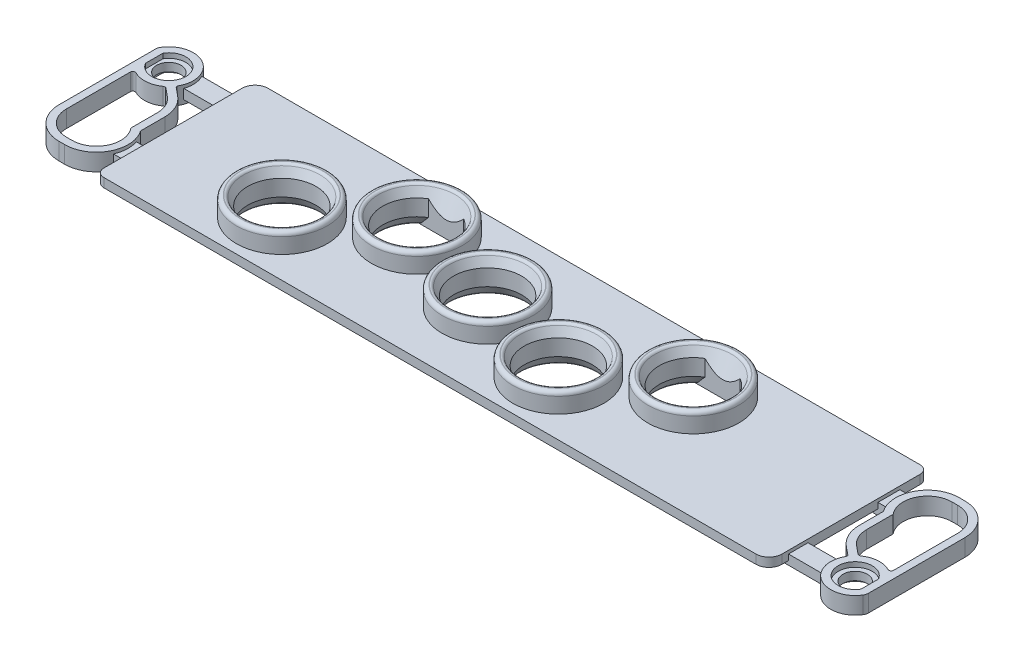
SolidWorks part; units mm, degrees
ref_plane "Front Plane" through (0, 0, 0) normal (0, 0, 1) x (1, 0, 0)
ref_plane "Top Plane" through (0, 0, 0) normal (0, 1, 0) x (1, 0, 0)
ref_plane "Right Plane" through (0, 0, 0) normal (1, 0, 0) x (0, 0, -1)
ref_plane "Plane1" through (0, 0, 0) normal (0, 1, 0) x (1, 0, 0)
sketch "Sketch1" plane through (0, 0, 0) normal (0, 1, 0) x (1, 0, 0)
  line L0 (-18.7, -4.9) -> (21.4, -4.9)
  line L1 (22.2, -4.1) -> (22.2, 4.4)
  line L2 (21.7, 4.9) -> (-18.4, 4.9)
  line L3 (-19.2, 4.1) -> (-19.2, -4.4)
  arc A0 (-19.2, -4.4) -> (-18.7, -4.9) centre (-18.7, -4.4) ccw
  arc A1 (21.4, -4.9) -> (22.2, -4.1) centre (21.4, -4.1) ccw
  arc A2 (22.2, 4.4) -> (21.7, 4.9) centre (21.7, 4.4) ccw
  arc A3 (-18.4, 4.9) -> (-19.2, 4.1) centre (-18.4, 4.1) ccw
extrude "Boss-Extrude1" add sketch "Sketch1" along normal blind 0.55
ref_plane "Plane2" through (0, 0, 0) normal (0, 0, 1) x (1, 0, 0)
sketch "Sketch2" plane through (0, 0, 0) normal (0, 0, 1) x (1, 0, 0)
  line L0 (20.349, 0) -> (20.9111, -0.5621)
  line L1 (21.1233, -0.65) -> (21.25, -0.65)
  line L2 (21.45, -0.45) -> (21.45, 0)
  line L3 (21.45, 0) -> (20.349, 0)
  arc A0 (20.9111, -0.5621) -> (21.1233, -0.65) centre (21.1233, -0.35) ccw
  arc A1 (21.25, -0.65) -> (21.45, -0.45) centre (21.25, -0.45) ccw
extrude "Boss-Extrude2" add sketch "Sketch2" against normal blind 3.95 and the other way blind 3.95
ref_plane "Plane3" through (0, 0, 0) normal (0, 0, 1) x (1, 0, 0)
sketch "Sketch3" plane through (0, 0, 0) normal (0, 0, 1) x (1, 0, 0)
  line L0 (-18.25, -0.65) -> (-18.1233, -0.65)
  line L1 (-17.9111, -0.5621) -> (-17.349, 0)
  line L2 (-17.349, 0) -> (-18.45, 0)
  line L3 (-18.45, 0) -> (-18.45, -0.45)
  arc A0 (-18.45, -0.45) -> (-18.25, -0.65) centre (-18.25, -0.45) ccw
  arc A1 (-18.1233, -0.65) -> (-17.9111, -0.5621) centre (-18.1233, -0.35) ccw
extrude "Boss-Extrude3" add sketch "Sketch3" against normal blind 3.95 and the other way blind 3.95
ref_plane "Plane4" through (0, 0, 0) normal (0, 0, 1) x (1, 0, 0)
sketch "Sketch4" plane through (0, 0, 0) normal (0, 0, 1) x (1, 0, 0)
  line L0 (17.2, 0) -> (19.0199, 0)
  line L1 (19.0199, 0) -> (18.125, -1.55)
  line L2 (18.125, -1.55) -> (17.2, -1.55)
  line L3 (17.2, -1.55) -> (17.2, 0)
  line L4 (17.2, -1.55) -> (17.2, 0) construction
revolve "Revolve1" add sketch "Sketch4" angle 360 about L4
ref_plane "Plane5" through (0, 0, 3.15) normal (0, 0, 1) x (1, 0, 0)
sketch "Sketch5" plane through (0, 0, 3.15) normal (0, 0, 1) x (1, 0, 0)
  line L0 (-19.84, 0.35) -> (-19.84, -0.35)
  line L1 (-19.84, -0.35) -> (-18.45, -0.35)
  line L2 (-18.45, -0.35) -> (-18.45, 0.35)
  line L3 (-18.45, 0.35) -> (-19.84, 0.35)
extrude "Boss-Extrude4" add sketch "Sketch5" against normal blind 1.35
ref_plane "Plane6" through (0, 0, -3.7) normal (0, 0, 1) x (1, 0, 0)
sketch "Sketch6" plane through (0, 0, -3.7) normal (0, 0, 1) x (1, 0, 0)
  line L0 (-21.404, 0.35) -> (-21.404, -0.25)
  line L1 (-21.404, -0.25) -> (-18.45, -0.25)
  line L2 (-18.45, -0.25) -> (-18.45, 0.35)
  line L3 (-18.45, 0.35) -> (-21.404, 0.35)
extrude "Boss-Extrude5" add sketch "Sketch6" along normal blind 1.2
ref_plane "Plane7" through (0, -0.5, 0) normal (0, 1, 0) x (1, 0, 0)
sketch "Sketch7" plane through (0, -0.5, 0) normal (0, 1, 0) x (1, 0, 0)
  line L0 (-23.95, 3.5268) -> (-23.95, -2.4)
  line L1 (-22, -4.35) -> (-21.65, -4.35)
  line L2 (-20.05, -1.2853) -> (-20.05, 0.2)
  line L3 (-20.7634, 1.7078) -> (-21.2754, 2.1277)
  line L4 (-23.5, 1.5303) -> (-23.5, -2.4)
  line L5 (-22, -3.9) -> (-21.65, -3.9)
  line L6 (-20.5, -1.4369) -> (-20.5, 0.2)
  line L7 (-21.0488, 1.3598) -> (-21.5497, 1.7706)
  line L8 (-23.5, 3.5408) -> (-23.5, 2.4592)
  arc A0 (-23.95, -2.4) -> (-22, -4.35) centre (-22, -2.4) ccw
  arc A1 (-21.65, -4.35) -> (-20.05, -1.2853) centre (-21.65, -2.4) ccw
  arc A2 (-20.05, 0.2) -> (-20.7634, 1.7078) centre (-22, 0.2) ccw
  arc A3 (-21.2754, 2.1277) -> (-21.303, 2.2466) centre (-21.212, 2.205) cw
  arc A4 (-21.303, 2.2466) -> (-23.875, 3.7902) centre (-22.6, 3) ccw
  arc A5 (-23.875, 3.7902) -> (-23.95, 3.5268) centre (-23.45, 3.5268) ccw
  arc A6 (-23.5, -2.4) -> (-22, -3.9) centre (-22, -2.4) ccw
  arc A7 (-21.65, -3.9) -> (-20.5, -1.4369) centre (-21.65, -2.4) ccw
  arc A8 (-20.5, 0.2) -> (-21.0488, 1.3598) centre (-22, 0.2) ccw
  arc A9 (-21.5497, 1.7706) -> (-21.7316, 1.7769) centre (-21.6448, 1.6546) ccw
  arc A10 (-21.7316, 1.7769) -> (-23.2818, 1.6639) centre (-22.6, 3) cw
  arc A11 (-23.2818, 1.6639) -> (-23.5, 1.5303) centre (-23.35, 1.5303) ccw
  arc A12 (-23.5, 2.4592) -> (-23.5, 3.5408) centre (-22.6, 3) ccw
extrude "Boss-Extrude6" add sketch "Sketch7" along normal blind 1.05
ref_plane "Plane8" through (0, 0, 3.7) normal (0, 0, 1) x (1, 0, 0)
sketch "Sketch8" plane through (0, 0, 3.7) normal (0, 0, 1) x (1, 0, 0)
  line L0 (21.45, 0.35) -> (21.45, -0.25)
  line L1 (21.45, -0.25) -> (24.404, -0.25)
  line L2 (24.404, -0.25) -> (24.404, 0.35)
  line L3 (24.404, 0.35) -> (21.45, 0.35)
extrude "Boss-Extrude7" add sketch "Sketch8" against normal blind 1.2
ref_plane "Plane9" through (0, 0, -3.15) normal (0, 0, 1) x (1, 0, 0)
sketch "Sketch9" plane through (0, 0, -3.15) normal (0, 0, 1) x (1, 0, 0)
  line L0 (21.45, 0.35) -> (21.45, -0.35)
  line L1 (21.45, -0.35) -> (22.84, -0.35)
  line L2 (22.84, -0.35) -> (22.84, 0.35)
  line L3 (22.84, 0.35) -> (21.45, 0.35)
extrude "Boss-Extrude8" add sketch "Sketch9" along normal blind 1.35
ref_plane "Plane10" through (0, -0.5, 0) normal (0, 1, 0) x (1, 0, 0)
sketch "Sketch10" plane through (0, -0.5, 0) normal (0, 1, 0) x (1, 0, 0)
  line L0 (23.05, 1.2853) -> (23.05, -0.2)
  line L1 (23.7634, -1.7078) -> (24.2754, -2.1277)
  line L2 (26.95, -3.5268) -> (26.95, 2.4)
  line L3 (25, 4.35) -> (24.65, 4.35)
  line L4 (26.5, -3.5408) -> (26.5, -2.4592)
  line L5 (23.5, 1.4369) -> (23.5, -0.2)
  line L6 (24.0488, -1.3598) -> (24.5497, -1.7706)
  line L7 (26.5, -1.5303) -> (26.5, 2.4)
  line L8 (25, 3.9) -> (24.65, 3.9)
  arc A0 (24.65, 4.35) -> (23.05, 1.2853) centre (24.65, 2.4) ccw
  arc A1 (23.05, -0.2) -> (23.7634, -1.7078) centre (25, -0.2) ccw
  arc A2 (24.2754, -2.1277) -> (24.303, -2.2466) centre (24.212, -2.205) cw
  arc A3 (24.303, -2.2466) -> (26.875, -3.7902) centre (25.6, -3) ccw
  arc A4 (26.875, -3.7902) -> (26.95, -3.5268) centre (26.45, -3.5268) ccw
  arc A5 (26.95, 2.4) -> (25, 4.35) centre (25, 2.4) ccw
  arc A6 (26.5, -2.4592) -> (26.5, -3.5408) centre (25.6, -3) ccw
  arc A7 (24.65, 3.9) -> (23.5, 1.4369) centre (24.65, 2.4) ccw
  arc A8 (23.5, -0.2) -> (24.0488, -1.3598) centre (25, -0.2) ccw
  arc A9 (24.5497, -1.7706) -> (24.7316, -1.7769) centre (24.6448, -1.6546) ccw
  arc A10 (24.7316, -1.7769) -> (26.2818, -1.6639) centre (25.6, -3) cw
  arc A11 (26.2818, -1.6639) -> (26.5, -1.5303) centre (26.35, -1.5303) ccw
  arc A12 (26.5, 2.4) -> (25, 3.9) centre (25, 2.4) ccw
extrude "Boss-Extrude9" add sketch "Sketch10" along normal blind 1.05
ref_plane "Plane11" through (0, 0, -3) normal (0, 0, 1) x (1, 0, 0)
sketch "Sketch11" plane through (0, 0, -3) normal (0, 0, 1) x (1, 0, 0)
  line L0 (-23.7, 0.25) -> (-23.7, -0.25)
  line L1 (-23.7, -0.25) -> (-23.35, -0.25)
  line L2 (-23.35, -0.25) -> (-23.35, 0.25)
  line L3 (-23.35, 0.25) -> (-23.7, 0.25)
  line L4 (-22.6, 0.25) -> (-22.6, -0.25) construction
revolve "Revolve2" add sketch "Sketch11" angle 360 about L4
ref_plane "Plane12" through (0, 0, 3) normal (0, 0, 1) x (1, 0, 0)
sketch "Sketch12" plane through (0, 0, 3) normal (0, 0, 1) x (1, 0, 0)
  line L0 (24.5, 0.25) -> (24.5, -0.25)
  line L1 (24.5, -0.25) -> (24.85, -0.25)
  line L2 (24.85, -0.25) -> (24.85, 0.25)
  line L3 (24.85, 0.25) -> (24.5, 0.25)
  line L4 (25.6, 0.25) -> (25.6, -0.25) construction
revolve "Revolve3" add sketch "Sketch12" angle 360 about L4
ref_plane "Plane13" through (0, 0, 0) normal (0, 0, 1) x (1, 0, 0)
sketch "Sketch13" plane through (0, 0, 0) normal (0, 0, 1) x (1, 0, 0)
  line L0 (0, 1.75) -> (2.55, 1.75)
  line L1 (2.8, 1.5) -> (2.8, 0)
  line L2 (2.8, 0) -> (2.9, 0)
  line L3 (2.9, 0) -> (2.7721, -0.3513)
  line L4 (2.6312, -0.45) -> (0, -0.45)
  line L5 (0, -0.45) -> (0, 1.75)
  line L6 (0, -0.45) -> (0, 1.75) construction
  arc A0 (2.55, 1.75) -> (2.8, 1.5) centre (2.55, 1.5) cw
  arc A1 (2.7721, -0.3513) -> (2.6312, -0.45) centre (2.6312, -0.3) cw
revolve "Revolve4" add sketch "Sketch13" angle 360 about L6
ref_plane "Plane14" through (0, 0, 1.55) normal (0, 0, 1) x (1, 0, 0)
sketch "Sketch14" plane through (0, 0, 1.55) normal (0, 0, 1) x (1, 0, 0)
  line L0 (5.9, 1.75) -> (8.45, 1.75)
  line L1 (8.7, 1.5) -> (8.7, 0)
  line L2 (8.7, 0) -> (8.8, 0)
  line L3 (8.8, 0) -> (8.6721, -0.3513)
  line L4 (8.5312, -0.45) -> (5.9, -0.45)
  line L5 (5.9, -0.45) -> (5.9, 1.75)
  line L6 (5.9, -0.45) -> (5.9, 1.75) construction
  arc A0 (8.45, 1.75) -> (8.7, 1.5) centre (8.45, 1.5) cw
  arc A1 (8.6721, -0.3513) -> (8.5312, -0.45) centre (8.5312, -0.3) cw
revolve "Revolve5" add sketch "Sketch14" angle 360 about L6
ref_plane "Plane15" through (0, 0, 1.55) normal (0, 0, 1) x (1, 0, 0)
sketch "Sketch15" plane through (0, 0, 1.55) normal (0, 0, 1) x (1, 0, 0)
  line L0 (-11.1, 1.75) -> (-8.55, 1.75)
  line L1 (-8.3, 1.5) -> (-8.3, 0)
  line L2 (-8.3, 0) -> (-8.2, 0)
  line L3 (-8.2, 0) -> (-8.3279, -0.3513)
  line L4 (-8.4688, -0.45) -> (-11.1, -0.45)
  line L5 (-11.1, -0.45) -> (-11.1, 1.75)
  line L6 (-11.1, -0.45) -> (-11.1, 1.75) construction
  arc A0 (-8.55, 1.75) -> (-8.3, 1.5) centre (-8.55, 1.5) cw
  arc A1 (-8.3279, -0.3513) -> (-8.4688, -0.45) centre (-8.4688, -0.3) cw
revolve "Revolve6" add sketch "Sketch15" angle 360 about L6
ref_plane "Plane16" through (0, 0, -1.55) normal (0, 0, 1) x (1, 0, 0)
sketch "Sketch16" plane through (0, 0, -1.55) normal (0, 0, 1) x (1, 0, 0)
  line L0 (11.1, 1.75) -> (13.65, 1.75)
  line L1 (13.9, 1.5) -> (13.9, 0)
  line L2 (13.9, 0) -> (14, 0)
  line L3 (14, 0) -> (13.8721, -0.3513)
  line L4 (13.7312, -0.45) -> (11.1, -0.45)
  line L5 (11.1, -0.45) -> (11.1, 1.75)
  line L6 (11.1, -0.45) -> (11.1, 1.75) construction
  arc A0 (13.65, 1.75) -> (13.9, 1.5) centre (13.65, 1.5) cw
  arc A1 (13.8721, -0.3513) -> (13.7312, -0.45) centre (13.7312, -0.3) cw
revolve "Revolve7" add sketch "Sketch16" angle 360 about L6
ref_plane "Plane17" through (0, 0, -1.55) normal (0, 0, 1) x (1, 0, 0)
sketch "Sketch17" plane through (0, 0, -1.55) normal (0, 0, 1) x (1, 0, 0)
  line L0 (-5.9, 1.75) -> (-3.35, 1.75)
  line L1 (-3.1, 1.5) -> (-3.1, 0)
  line L2 (-3.1, 0) -> (-3, 0)
  line L3 (-3, 0) -> (-3.1279, -0.3513)
  line L4 (-3.2688, -0.45) -> (-5.9, -0.45)
  line L5 (-5.9, -0.45) -> (-5.9, 1.75)
  line L6 (-5.9, -0.45) -> (-5.9, 1.75) construction
  arc A0 (-3.35, 1.75) -> (-3.1, 1.5) centre (-3.35, 1.5) cw
  arc A1 (-3.1279, -0.3513) -> (-3.2688, -0.45) centre (-3.2688, -0.3) cw
revolve "Revolve8" add sketch "Sketch17" angle 360 about L6
ref_plane "Plane18" through (0, 0, 0) normal (0, 0, 1) x (1, 0, 0)
sketch "Sketch18" plane through (0, 0, 0) normal (0, 0, 1) x (1, 0, 0)
  line L0 (0, 1.75) -> (2.5283, 1.75)
  line L1 (2.3501, 1.6408) -> (2.1, 1.15)
  line L2 (2.1, 1.15) -> (2.1, 0.15)
  line L3 (2.1, 0.15) -> (2.3362, -0.3135)
  line L4 (2.5589, -0.45) -> (0, -0.45)
  line L5 (0, -0.45) -> (0, 1.75)
  line L6 (0, -0.45) -> (0, 1.75) construction
  arc A0 (2.5283, 1.75) -> (2.3501, 1.6408) centre (2.5283, 1.55) ccw
  arc A1 (2.3362, -0.3135) -> (2.5589, -0.45) centre (2.5589, -0.2) ccw
revolve "Cut-Revolve1" cut sketch "Sketch18" angle 360 about L6
ref_plane "Plane19" through (0, 0, 1.55) normal (0, 0, 1) x (1, 0, 0)
sketch "Sketch19" plane through (0, 0, 1.55) normal (0, 0, 1) x (1, 0, 0)
  line L0 (5.9, 1.75) -> (8.4283, 1.75)
  line L1 (8.2501, 1.6408) -> (8, 1.15)
  line L2 (8, 1.15) -> (8, 0.15)
  line L3 (8, 0.15) -> (8.2362, -0.3135)
  line L4 (8.4589, -0.45) -> (5.9, -0.45)
  line L5 (5.9, -0.45) -> (5.9, 1.75)
  line L6 (5.9, -0.45) -> (5.9, 1.75) construction
  arc A0 (8.4283, 1.75) -> (8.2501, 1.6408) centre (8.4283, 1.55) ccw
  arc A1 (8.2362, -0.3135) -> (8.4589, -0.45) centre (8.4589, -0.2) ccw
revolve "Cut-Revolve2" cut sketch "Sketch19" angle 360 about L6
ref_plane "Plane20" through (0, 0, 1.55) normal (0, 0, 1) x (1, 0, 0)
sketch "Sketch20" plane through (0, 0, 1.55) normal (0, 0, 1) x (1, 0, 0)
  line L0 (-11.1, 1.75) -> (-8.5717, 1.75)
  line L1 (-8.7499, 1.6408) -> (-9, 1.15)
  line L2 (-9, 1.15) -> (-9, 0.15)
  line L3 (-9, 0.15) -> (-8.7638, -0.3135)
  line L4 (-8.5411, -0.45) -> (-11.1, -0.45)
  line L5 (-11.1, -0.45) -> (-11.1, 1.75)
  line L6 (-11.1, -0.45) -> (-11.1, 1.75) construction
  arc A0 (-8.5717, 1.75) -> (-8.7499, 1.6408) centre (-8.5717, 1.55) ccw
  arc A1 (-8.7638, -0.3135) -> (-8.5411, -0.45) centre (-8.5411, -0.2) ccw
revolve "Cut-Revolve3" cut sketch "Sketch20" angle 360 about L6
ref_plane "Plane21" through (0, 0, -1.55) normal (0, 0, 1) x (1, 0, 0)
sketch "Sketch21" plane through (0, 0, -1.55) normal (0, 0, 1) x (1, 0, 0)
  line L0 (11.1, 1.75) -> (13.6283, 1.75)
  line L1 (13.4501, 1.6408) -> (13.2, 1.15)
  line L2 (13.2, 1.15) -> (13.2, 0.15)
  line L3 (13.2, 0.15) -> (13.4362, -0.3135)
  line L4 (13.6589, -0.45) -> (11.1, -0.45)
  line L5 (11.1, -0.45) -> (11.1, 1.75)
  line L6 (11.1, -0.45) -> (11.1, 1.75) construction
  arc A0 (13.6283, 1.75) -> (13.4501, 1.6408) centre (13.6283, 1.55) ccw
  arc A1 (13.4362, -0.3135) -> (13.6589, -0.45) centre (13.6589, -0.2) ccw
revolve "Cut-Revolve4" cut sketch "Sketch21" angle 360 about L6
ref_plane "Plane22" through (0, 0, -1.55) normal (0, 0, 1) x (1, 0, 0)
sketch "Sketch22" plane through (0, 0, -1.55) normal (0, 0, 1) x (1, 0, 0)
  line L0 (-5.9, 1.75) -> (-3.3717, 1.75)
  line L1 (-3.5499, 1.6408) -> (-3.8, 1.15)
  line L2 (-3.8, 1.15) -> (-3.8, 0.15)
  line L3 (-3.8, 0.15) -> (-3.5638, -0.3135)
  line L4 (-3.3411, -0.45) -> (-5.9, -0.45)
  line L5 (-5.9, -0.45) -> (-5.9, 1.75)
  line L6 (-5.9, -0.45) -> (-5.9, 1.75) construction
  arc A0 (-3.3717, 1.75) -> (-3.5499, 1.6408) centre (-3.3717, 1.55) ccw
  arc A1 (-3.5638, -0.3135) -> (-3.3411, -0.45) centre (-3.3411, -0.2) ccw
revolve "Cut-Revolve5" cut sketch "Sketch22" angle 360 about L6
ref_plane "Plane23" through (0, -0.45, 0) normal (0, 1, 0) x (1, 0, 0)
sketch "Sketch23" plane through (0, -0.45, 0) normal (0, 1, 0) x (1, 0, 0)
  line L0 (-7.7762, 3.35) -> (-4.0238, 3.35)
  arc A0 (-4.0238, 3.35) -> (-7.7762, 3.35) centre (-5.9, 1.55) ccw
extrude "Boss-Extrude10" add sketch "Sketch23" along normal blind 2.05
ref_plane "Plane24" through (0, 0, -1.55) normal (0, 0, 1) x (1, 0, 0)
sketch "Sketch24" plane through (0, 0, -1.55) normal (0, 0, 1) x (1, 0, 0)
  line L0 (-5.9, 1.75) -> (-3.3717, 1.75)
  line L1 (-3.5499, 1.6408) -> (-4.5643, -0.35)
  line L2 (-4.5643, -0.35) -> (-5.9, -0.35)
  line L3 (-5.9, -0.35) -> (-5.9, 1.75)
  line L4 (-5.9, -0.45) -> (-5.9, 1.75) construction
  arc A0 (-3.3717, 1.75) -> (-3.5499, 1.6408) centre (-3.3717, 1.55) ccw
revolve "Cut-Revolve6" cut sketch "Sketch24" angle 360 about L4
ref_plane "Plane25" through (0, -0.45, 0) normal (0, 1, 0) x (1, 0, 0)
sketch "Sketch25" plane through (0, -0.45, 0) normal (0, 1, 0) x (1, 0, 0)
  line L0 (9.2238, 3.35) -> (12.9762, 3.35)
  arc A0 (12.9762, 3.35) -> (9.2238, 3.35) centre (11.1, 1.55) ccw
extrude "Boss-Extrude11" add sketch "Sketch25" along normal blind 2.05
ref_plane "Plane26" through (0, 0, -1.55) normal (0, 0, 1) x (1, 0, 0)
sketch "Sketch26" plane through (0, 0, -1.55) normal (0, 0, 1) x (1, 0, 0)
  line L0 (11.1, 1.75) -> (13.6283, 1.75)
  line L1 (13.4501, 1.6408) -> (12.4357, -0.35)
  line L2 (12.4357, -0.35) -> (11.1, -0.35)
  line L3 (11.1, -0.35) -> (11.1, 1.75)
  line L4 (11.1, -0.45) -> (11.1, 1.75) construction
  arc A0 (13.6283, 1.75) -> (13.4501, 1.6408) centre (13.6283, 1.55) ccw
revolve "Cut-Revolve7" cut sketch "Sketch26" angle 360 about L4
ref_plane "Plane27" through (0, -0.45, 0) normal (0, 1, 0) x (1, 0, 0)
sketch "Sketch27" plane through (0, -0.45, 0) normal (0, 1, 0) x (1, 0, 0)
  line L0 (7.7762, -3.35) -> (4.0238, -3.35)
  arc A0 (4.0238, -3.35) -> (7.7762, -3.35) centre (5.9, -1.55) ccw
extrude "Boss-Extrude12" add sketch "Sketch27" along normal blind 2.05
ref_plane "Plane28" through (0, 0, 1.55) normal (0, 0, 1) x (1, 0, 0)
sketch "Sketch28" plane through (0, 0, 1.55) normal (0, 0, 1) x (1, 0, 0)
  line L0 (5.9, 1.75) -> (8.4283, 1.75)
  line L1 (8.2501, 1.6408) -> (7.2357, -0.35)
  line L2 (7.2357, -0.35) -> (5.9, -0.35)
  line L3 (5.9, -0.35) -> (5.9, 1.75)
  line L4 (5.9, -0.45) -> (5.9, 1.75) construction
  arc A0 (8.4283, 1.75) -> (8.2501, 1.6408) centre (8.4283, 1.55) ccw
revolve "Cut-Revolve8" cut sketch "Sketch28" angle 360 about L4
ref_plane "Plane29" through (0, -0.45, 0) normal (0, 1, 0) x (1, 0, 0)
sketch "Sketch29" plane through (0, -0.45, 0) normal (0, 1, 0) x (1, 0, 0)
  line L0 (-9.2238, -3.35) -> (-12.9762, -3.35)
  arc A0 (-12.9762, -3.35) -> (-9.2238, -3.35) centre (-11.1, -1.55) ccw
extrude "Boss-Extrude13" add sketch "Sketch29" along normal blind 2.05
ref_plane "Plane30" through (0, 0, 1.55) normal (0, 0, 1) x (1, 0, 0)
sketch "Sketch30" plane through (0, 0, 1.55) normal (0, 0, 1) x (1, 0, 0)
  line L0 (-11.1, 1.75) -> (-8.5717, 1.75)
  line L1 (-8.7499, 1.6408) -> (-9.7643, -0.35)
  line L2 (-9.7643, -0.35) -> (-11.1, -0.35)
  line L3 (-11.1, -0.35) -> (-11.1, 1.75)
  line L4 (-11.1, -0.45) -> (-11.1, 1.75) construction
  arc A0 (-8.5717, 1.75) -> (-8.7499, 1.6408) centre (-8.5717, 1.55) ccw
revolve "Cut-Revolve9" cut sketch "Sketch30" angle 360 about L4
